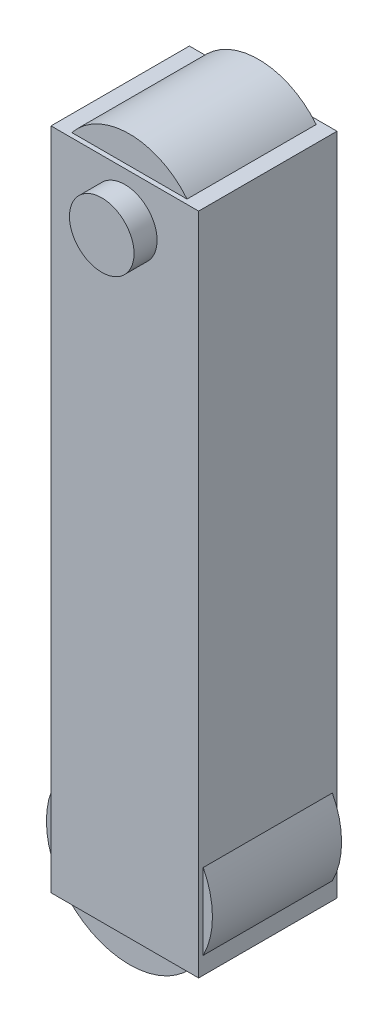
SolidWorks part; units mm, degrees
ref_plane "Front Plane" through (0, 0, 0) normal (0, 0, 1) x (1, 0, 0)
ref_plane "Top Plane" through (0, 0, 0) normal (0, 1, 0) x (1, 0, 0)
ref_plane "Right Plane" through (0, 0, 0) normal (1, 0, 0) x (0, 0, -1)
sketch "Sketch1" plane through (0, 0, 0) normal (0, 0, 1) x (1, 0, 0)
  line L1 (-16, 64) -> (16, 64)
  line L2 (-16, 64) -> (-16, 208)
  line L3 (-16, 208) -> (16, 208)
  line L4 (16, 64) -> (16, 208)
extrude "Boss-Extrude1" add sketch "Sketch1" along normal mid plane 30
sketch "Sketch2" plane through (0, 0, 0) normal (0, 0, 1) x (1, 0, 0)
  circle A0 centre (0, 76) radius 18
extrude "Boss-Extrude2" add sketch "Sketch2" along normal mid plane 28
sketch "Sketch3" plane through (0, 0, 0) normal (0, 0, 1) x (1, 0, 0)
  circle A0 centre (0, 198) radius 16
extrude "Boss-Extrude3" add sketch "Sketch3" along normal mid plane 28
sketch "Sketch4" plane through (0, 0, 0) normal (0, 0, 1) x (1, 0, 0)
  circle A0 centre (0, 76) radius 8.25
extrude "Cut-Extrude1" cut sketch "Sketch4" against normal through all
sketch "Sketch5" plane through (0, 0, 0) normal (0, 0, 1) x (1, 0, 0)
  circle A0 centre (0, 198) radius 7
extrude "Boss-Extrude4" add sketch "Sketch5" along normal mid plane 40
sketch "Sketch6" plane through (0, 0, 0) normal (0, 0, 1) x (1, 0, 0)
  circle A0 centre (0, 118) radius 10
  circle A1 centre (0, 155) radius 10
extrude "Cut-Extrude2" cut sketch "Sketch6" against normal through all
